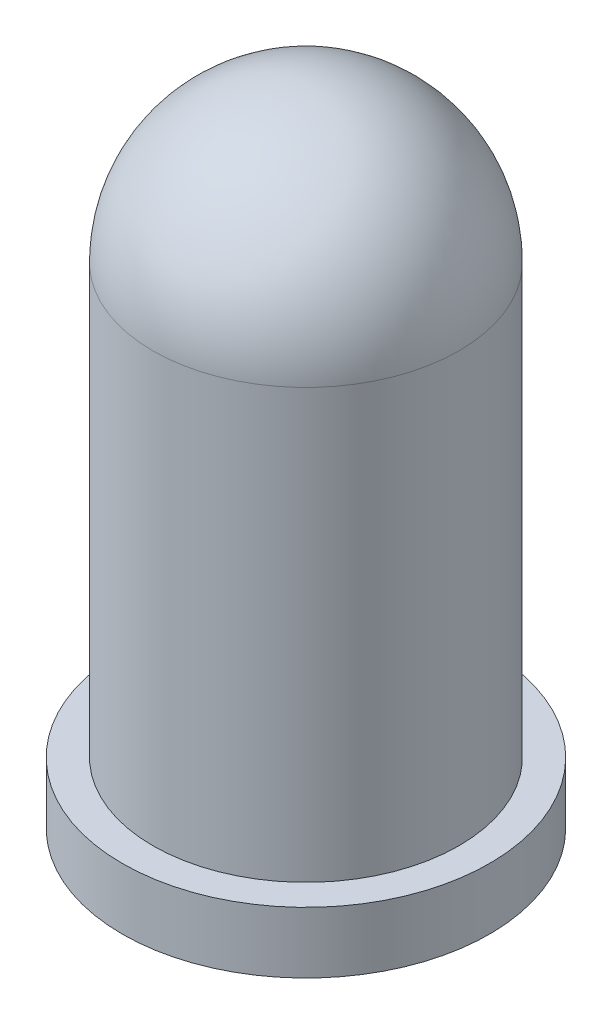
SolidWorks part; units mm, degrees
ref_plane "Front Plane" through (0, 0, 0) normal (0, 0, 1) x (1, 0, 0)
ref_plane "Top Plane" through (0, 0, 0) normal (0, 1, 0) x (1, 0, 0)
ref_plane "Right Plane" through (0, 0, 0) normal (1, 0, 0) x (0, 0, -1)
sketch "Sketch1" plane through (0, 0, 0) normal (0, 0, 1) x (1, 0, 0)
  line L0 (0, 78.4134) -> (0, -46.4769) construction
  line L1 (-3, 42.5227) -> (3, 42.5227)
  line L2 (-3, 42.5227) -> (-3, 43.5227)
  line L3 (-3, 43.5227) -> (-2.5, 43.5227)
  line L4 (3, 42.5227) -> (3, 43.5227)
  line L5 (-2.5, 43.5227) -> (-2.5, 50.5227)
  line L6 (2.5, 50.5227) -> (2.5, 43.5227)
  line L7 (2.5, 43.5227) -> (3, 43.5227)
  arc A0 (-2.5, 50.5227) -> (2.5, 50.5227) centre (0, 50.5227) cw
  dimension "D1" = 2.5
  dimension "D2" = 7
  dimension "D3" = 1
  dimension "D4" = 6
revolve "Revolve1" add sketch "Sketch1" angle 360 about L0
